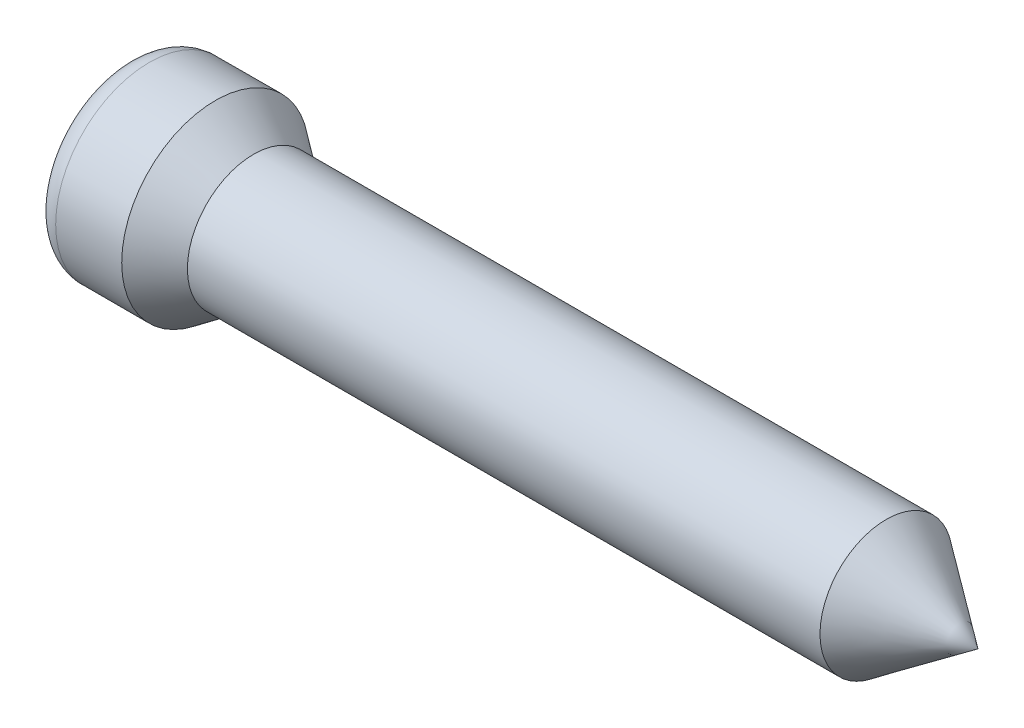
SolidWorks part; units mm, degrees
ref_plane "Front Plane" through (0, 0, 0) normal (0, 0, 1) x (1, 0, 0)
ref_plane "Top Plane" through (0, 0, 0) normal (0, 1, 0) x (1, 0, 0)
ref_plane "Right Plane" through (0, 0, 0) normal (1, 0, 0) x (0, 0, -1)
sketch "Sketch1" plane through (0, 0, 0) normal (0, 0, 1) x (1, 0, 0)
  line L0 (0, 0) -> (23.495, 0)
  line L1 (23.495, 0) -> (20.5088, 2.1528)
  line L2 (20.5088, 2.1528) -> (-0.0652, 2.1528)
  line L3 (-0.0652, 2.1528) -> (-1.307, 3.048)
  line L4 (-1.307, 3.048) -> (-4.2164, 3.048)
  line L5 (-4.2164, 3.048) -> (-4.2164, 0)
  line L6 (-4.2164, 0) -> (0, 0)
  line L7 (20.5088, 2.1528) -> (20.5088, 0) construction
  line L8 (-0.0652, 0) -> (-0.0652, 2.1528) construction
  dimension "D1" = 23.495
  dimension "D2" = 3.048
  dimension "D3" = 4.2164
  dimension "D4" = 20.574
revolve "Revolve1" add sketch "Sketch1" angle 360 about L6
fillet "Fillet1" radius 0.762 1 edges at (-4.2164, 0, 3.048)
